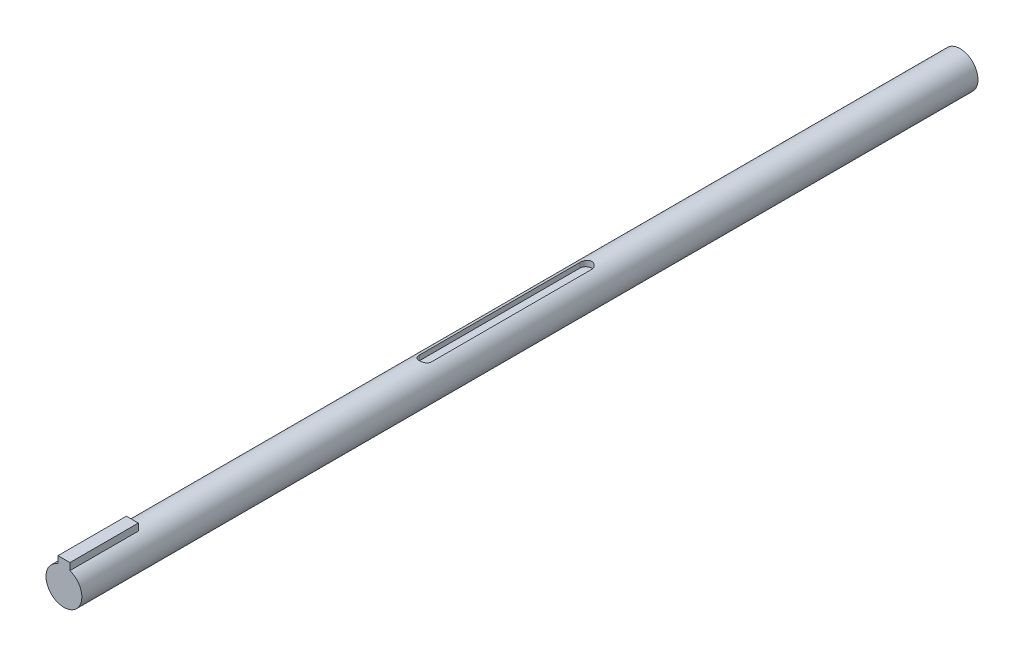
SolidWorks part; units mm, degrees
ref_plane "前视基准面" through (0, 0, 0) normal (0, 0, 1) x (1, 0, 0)
ref_plane "上视基准面" through (0, 0, 0) normal (0, 1, 0) x (1, 0, 0)
ref_plane "右视基准面" through (0, 0, 0) normal (1, 0, 0) x (0, 0, -1)
sketch "草图1" plane through (0, 0, 0) normal (0, 0, 1) x (1, 0, 0)
  circle A0 centre (0, 0) radius 6
  dimension "D1" = 12
extrude "凸台-拉伸1" add sketch "草图1" along normal blind 300
sketch "草图2" plane through (0, 0, 300) normal (0, 0, 1) x (1, 0, 0)
  line L0 (0, 4.0502) -> (0, -0.2748) construction
  line L1 (-2, 8) -> (2, 8)
  line L2 (-2, 8) -> (-2, 2.5831)
  line L3 (-2, 2.5831) -> (2, 2.5831)
  line L4 (2, 8) -> (2, 2.5831)
  line L5 (-2, 8) -> (2, 2.5831) construction
  line L6 (-2, 2.5831) -> (2, 8) construction
  circle A1 centre (0, 0) radius 6 construction
  point P0 (0, 5.2916)
  point P8 (0, 0)
  dimension "D1" = 4
  dimension "D2" = 14
extrude "凸台-拉伸2" add sketch "草图2" against normal blind 22.91
sketch "草图3" plane through (0, 0, 0) normal (0, 1, 0) x (1, 0, 0)
  line L0 (0, -125.298) -> (0, -179.002) construction
  line L1 (2, -125.298) -> (2, -179.002)
  line L2 (-2, -125.298) -> (-2, -179.002)
  arc A0 (2, -125.298) -> (-2, -125.298) centre (0, -125.298) ccw
  arc A1 (-2, -179.002) -> (2, -179.002) centre (0, -179.002) ccw
  point P3 (0, -152.15)
  dimension "D1" = 4
extrude "切除-拉伸1" cut sketch "草图3" against normal blind 2 from offset 6
